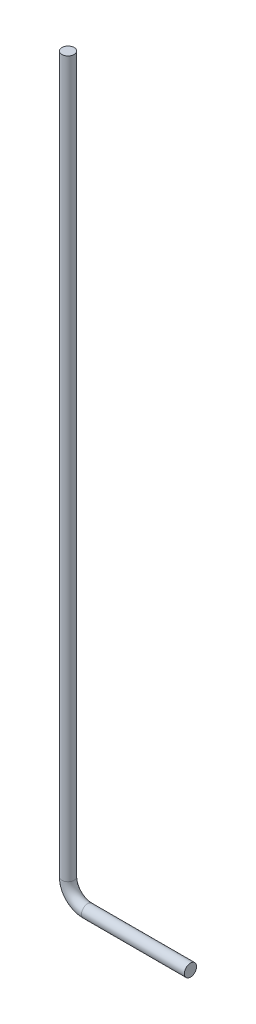
SolidWorks part; units mm, degrees
ref_plane "Plano frontal" through (0, 0, 0) normal (0, 0, 1) x (1, 0, 0)
ref_plane "Plano superior" through (0, 0, 0) normal (0, 1, 0) x (1, 0, 0)
ref_plane "Plano direito" through (0, 0, 0) normal (1, 0, 0) x (0, 0, -1)
sketch "Esboço1" plane through (0, 0, 0) normal (0, 0, 1) x (1, 0, 0)
  line L0 (0, 8) -> (0, 300)
  line L1 (8, 0) -> (50, 0)
  arc A0 (0, 8) -> (8, 0) centre (8, 8) ccw
sweep "Varredura2" add path "Esboço1" circular profile diameter 5 parameters "D3"=5
